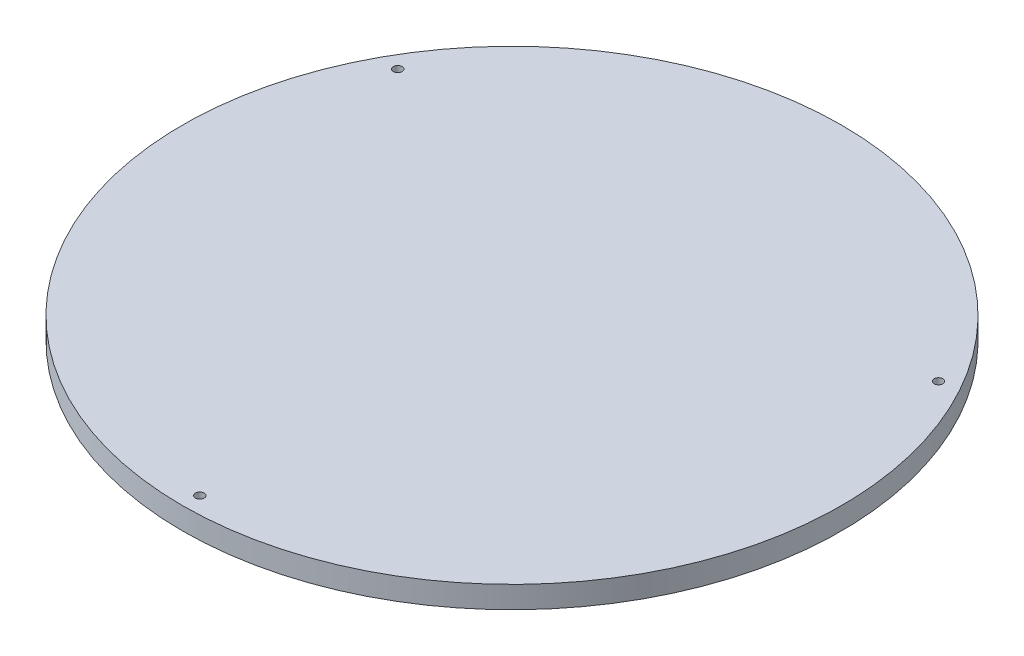
SolidWorks part; units mm, degrees
material "1060 Alloy"
ref_plane "Front Plane" through (0, 0, 0) normal (0, 0, 1) x (1, 0, 0)
ref_plane "Top Plane" through (0, 0, 0) normal (0, 1, 0) x (1, 0, 0)
ref_plane "Right Plane" through (0, 0, 0) normal (1, 0, 0) x (0, 0, -1)
sketch "Sketch1" plane through (0, 0, 0) normal (0, 1, 0) x (1, 0, 0)
  circle A0 centre (0, 0) radius 150
  point P15 (0, 0)
extrude "Boss-Extrude1" add sketch "Sketch1" along normal blind 10
sketch "Sketch2" plane through (0, 10, 0) normal (0, 1, 0) x (1, 0, 0)
  line L3 (0, 0) -> (0, -155.7893) construction
  line L4 (0, 0) -> (-134.9175, 77.8947) construction
  line L5 (0, 0) -> (134.9175, 77.8947) construction
  circle A13 centre (-123.0621, 71.05) radius 2
  circle A14 centre (123.0621, 71.05) radius 2
  circle A15 centre (0, -142.0999) radius 2
  point P8 (0, 0)
  point P33 (0, 0)
  point P34 (0, 0)
  point P37 (0, 0)
  point P38 (0, 0)
  point P44 (0, 0)
  dimension "D7" = 4
  dimension "D6" = 3
  dimension "D8" = 3
extrude "Cut-Extrude1" cut sketch "Sketch2" against normal blind 10
